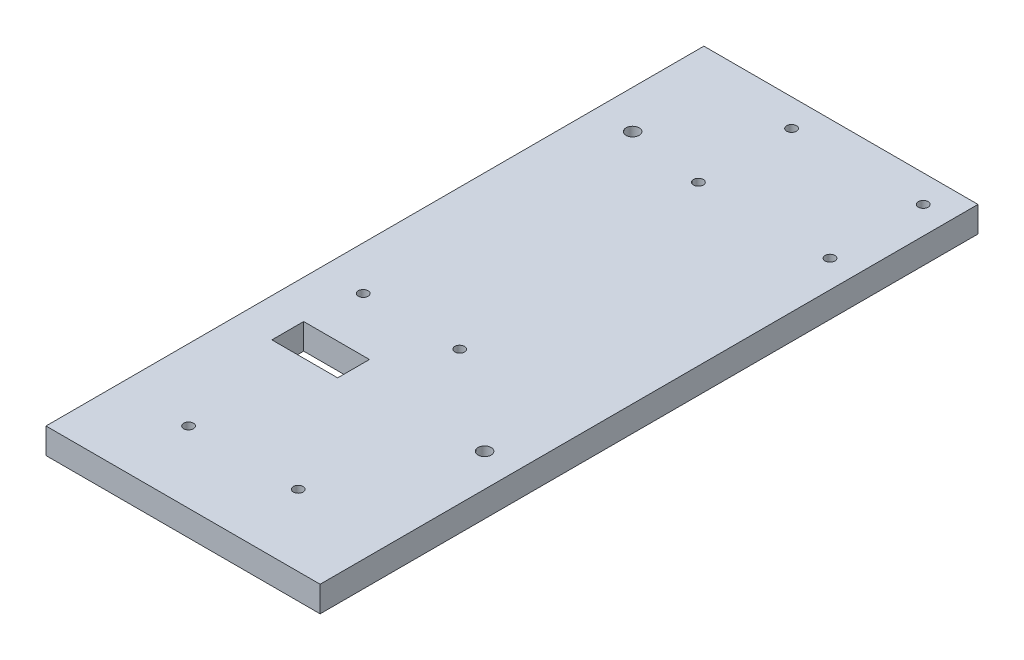
SolidWorks part; units mm, degrees
material "Acrylic (Medium-high impact)"
ref_plane "Front" through (0, 0, 0) normal (0, 0, 1) x (1, 0, 0)
ref_plane "Top" through (0, 0, 0) normal (0, 1, 0) x (1, 0, 0)
ref_plane "Right" through (0, 0, 0) normal (1, 0, 0) x (0, 0, -1)
sketch "Sketch1" plane through (0, 0, 0) normal (0, 1, 0) x (1, 0, 0)
  line L1 (0, 0) -> (63.5, 0)
  line L2 (0, 0) -> (0, 152.4)
  line L3 (0, 152.4) -> (63.5, 152.4)
  line L4 (63.5, 0) -> (63.5, 152.4)
  dimension "D1" = 63.5
  dimension "D2" = 152.4
extrude "Boss-Extrude1" add sketch "Sketch1" along normal blind 5.9436
sketch "Sketch2" plane through (0, 0, 0) normal (0, 1, 0) x (1, 0, 0)
  line L1 (26.67, 124.46) -> (57.15, 124.46) construction
  line L2 (26.67, 124.46) -> (26.67, 146.05) construction
  line L3 (26.67, 146.05) -> (57.15, 146.05) construction
  line L4 (57.15, 124.46) -> (57.15, 146.05) construction
  line L7 (63.5, 152.4) -> (0, 152.4) construction
  line L9 (63.5, 0) -> (63.5, 152.4) construction
  circle A0 centre (26.67, 124.46) radius 1.1303
  circle A1 centre (26.67, 146.05) radius 1.1303
  circle A2 centre (57.15, 146.05) radius 1.1303
  circle A3 centre (57.15, 124.46) radius 1.1303
  dimension "D5" = 2.2606
  dimension "D1" = 6.35
  dimension "D2" = 6.35
  dimension "D3" = 21.59
  dimension "D4" = 30.48
extrude "Cut-Extrude1" [suppressed] cut sketch "Sketch2" along normal through all
sketch "Sketch3" plane through (0, 5.9436, 0) normal (0, 1, 0) x (1, 0, 0)
  line L0 (63.5, 152.4) -> (0, 152.4) construction
  line L1 (0, 152.4) -> (0, 0) construction
  circle A0 centre (10.16, 73.4314) radius 1.1303
  circle A1 centre (32.385, 73.4314) radius 1.1303
  dimension "D1" = 78.9686
  dimension "D4" = 2.2606
  dimension "D2" = 10.16
  dimension "D3" = 22.225
extrude "Cut-Extrude2" [suppressed] cut sketch "Sketch3" against normal through all
sketch "Sketch4" plane through (0, 5.9436, 0) normal (0, 1, 0) x (1, 0, 0)
  line L0 (0, 152.4) -> (0, 0) construction
  line L1 (8.89, 50.8) -> (24.13, 50.8)
  line L2 (8.89, 50.8) -> (8.89, 43.434)
  line L3 (8.89, 43.434) -> (24.13, 43.434)
  line L4 (24.13, 50.8) -> (24.13, 43.434)
  line L5 (8.89, 50.8) -> (24.13, 43.434) construction
  line L6 (8.89, 43.434) -> (24.13, 50.8) construction
  line L10 (63.5, 152.4) -> (0, 152.4) construction
  point P0 (16.51, 47.117)
  dimension "D1" = 16.51
  dimension "D2" = 15.24
  dimension "D3" = 7.366
  dimension "D4" = 101.6
extrude "Cut-Extrude3" cut sketch "Sketch4" against normal through all
sketch "Sketch5" plane through (0, 5.9436, 0) normal (0, 1, 0) x (1, 0, 0)
  line L0 (63.5, 0) -> (63.5, 152.4) construction
  line L1 (0, 0) -> (63.5, 0) construction
  circle A0 centre (16.51, 12.7) radius 1.1303
  circle A1 centre (41.91, 12.7) radius 1.1303
  dimension "D1" = 25.4
  dimension "D4" = 2.2606
  dimension "D2" = 21.59
  dimension "D3" = 12.7
extrude "Cut-Extrude4" [suppressed] cut sketch "Sketch5" against normal through all
hole_wizard "#4-40 Tapped Hole1" positions "Sketch7" profile "Sketch8" tap size "#4-40" standard "ANSI Inch" end condition through all
sketch "Sketch7" plane through (0, 5.9436, 0) normal (0, 1, 0) x (1, 0, 0)
  line L0 (63.5, 152.4) -> (0, 152.4) construction
  line L1 (63.5, 0) -> (63.5, 152.4) construction
  point P0 (57.15, 146.05)
  point P2 (57.15, 124.46)
  point P4 (26.67, 124.46)
  point P6 (26.67, 146.05)
  dimension "D1" = 21.59
  dimension "D2" = 30.48
  dimension "D3" = 6.35
  dimension "D4" = 6.35
sketch "Sketch8" plane through (57.15, 5.9436, -146.05) normal (1, 0, 0) x (0, 0, 1)
  line L0 (0, 0) -> (0, 5.9436)
  line L1 (0, 5.9436) -> (1.1303, 5.9436)
  line L2 (1.1303, 5.9436) -> (1.1303, 0)
  line L5 (1.1303, 0) -> (0, 0)
  line L11 (0, -6.35) -> (0, 107.95) construction
  dimension "Thread Major Dia." = 2.2606
  dimension "Thru Tap Drill Depth" = 5.9436
hole_wizard "#4-40 Tapped Hole2" positions "Sketch9" profile "Sketch10" tap size "#4-40" standard "ANSI Inch" end condition through all
sketch "Sketch9" plane through (0, 5.9436, 0) normal (0, 1, 0) x (1, 0, 0)
  line L1 (0, 152.4) -> (0, 0) construction
  line L3 (63.5, 152.4) -> (0, 152.4) construction
  point P0 (32.512, 63.3222)
  point P2 (10.16, 63.3222)
  dimension "D1" = 22.352
  dimension "D2" = 89.0778
  dimension "D3" = 10.16
sketch "Sketch10" plane through (32.512, 5.9436, -63.3222) normal (1, 0, 0) x (0, 0, 1)
  line L0 (0, 0) -> (0, 5.9436)
  line L1 (0, 5.9436) -> (1.1303, 5.9436)
  line L2 (1.1303, 5.9436) -> (1.1303, 0)
  line L5 (1.1303, 0) -> (0, 0)
  line L11 (0, -6.35) -> (0, 107.95) construction
  dimension "Thread Major Dia." = 2.2606
  dimension "Thru Tap Drill Depth" = 5.9436
hole_wizard "#4-40 Tapped Hole3" positions "Sketch11" profile "Sketch12" tap size "#4-40" standard "ANSI Inch" end condition through all
sketch "Sketch11" plane through (0, 5.9436, 0) normal (0, 1, 0) x (1, 0, 0)
  line L1 (63.5, 0) -> (63.5, 152.4) construction
  line L4 (8.89, 50.8) -> (24.13, 50.8) construction
  point P0 (41.91, 16.51)
  point P2 (16.51, 16.51)
  point P17 (16.51, 50.8)
  dimension "D1" = 25.4
  dimension "D2" = 34.29
  dimension "D3" = 21.59
sketch "Sketch12" plane through (41.91, 5.9436, -16.51) normal (1, 0, 0) x (0, 0, 1)
  line L0 (0, 0) -> (0, 5.9436)
  line L1 (0, 5.9436) -> (1.1303, 5.9436)
  line L2 (1.1303, 5.9436) -> (1.1303, 0)
  line L5 (1.1303, 0) -> (0, 0)
  line L11 (0, -6.35) -> (0, 107.95) construction
  dimension "Thread Major Dia." = 2.2606
  dimension "Thru Tap Drill Depth" = 5.9436
sketch "Sketch13" plane through (0, 5.9436, 0) normal (0, 1, 0) x (1, 0, 0)
  line L0 (0, 0) -> (63.5, 0) construction
  circle A0 centre (8.89, 127) radius 1.524
  circle A1 centre (55.88, 45.72) radius 1.524
  point P4 (35.4558, 92.1942)
  point P9 (53.3852, 40.2034)
  point P12 (-48.7146, 77.7697)
  dimension "D1" = 3.048
  dimension "D4" = 3.048
  dimension "D2" = 127
  dimension "D3" = 7.62
  dimension "D5" = 46.99
  dimension "D6" = 81.28
extrude "Cut-Extrude5" cut sketch "Sketch13" against normal through all
